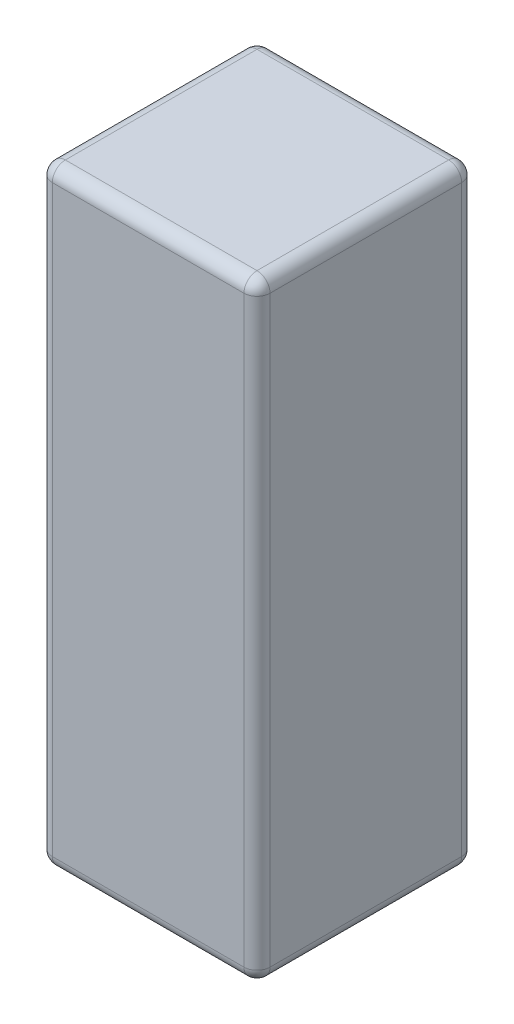
SolidWorks part; units mm, degrees
ref_plane "Спереди" through (0, 0, 0) normal (0, 0, 1) x (1, 0, 0)
ref_plane "Сверху" through (0, 0, 0) normal (0, 1, 0) x (1, 0, 0)
ref_plane "Справа" through (0, 0, 0) normal (1, 0, 0) x (0, 0, -1)
other "Configuration Table"
sketch "Эскиз1" plane through (0, 0, 0) normal (0, 1, 0) x (1, 0, 0)
  line L1 (0, 0) -> (50, 0)
  line L2 (0, 0) -> (0, 50)
  line L3 (0, 50) -> (50, 50)
  line L4 (50, 0) -> (50, 50)
  dimension "D1" = 50
  dimension "D2" = 50
extrude "Бобышка-Вытянуть1" add sketch "Эскиз1" along normal blind 140
fillet "Скругление1" radius 3 12 edges at (50, 70, 0) (50, 70, -50) (0, 70, -50) (0, 70, 0) (25, 0, 0) (50, 0, -25) (25, 0, -50) (0, 0, -25) (25, 140, -50) (50, 140, -25) (25, 140, 0) (0, 140, -25)
